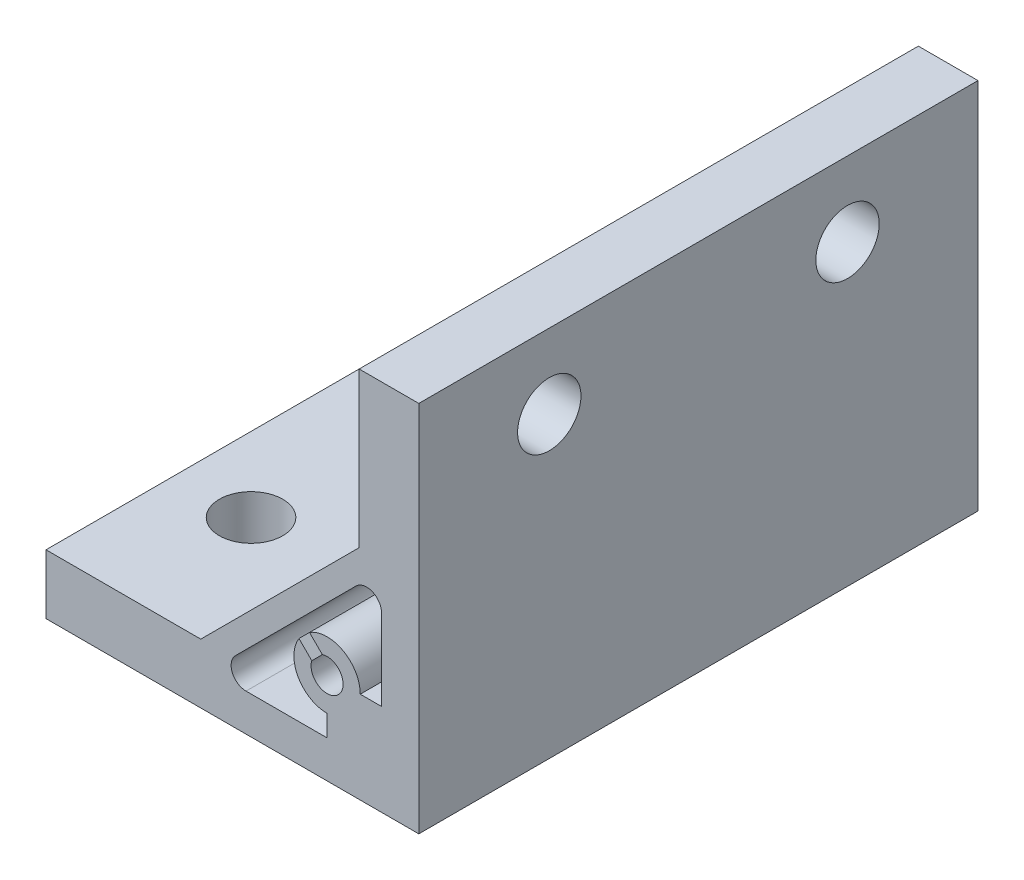
SolidWorks part; units mm, degrees
ref_plane "前视基准面" through (0, 0, 0) normal (0, 0, 1) x (1, 0, 0)
ref_plane "上视基准面" through (0, 0, 0) normal (0, 1, 0) x (1, 0, 0)
ref_plane "右视基准面" through (0, 0, 0) normal (1, 0, 0) x (0, 0, -1)
sketch "草图1" plane through (0, 0, 0) normal (0, 0, 1) x (1, 0, 0)
  line B0 (0, 0) -> (50, 0)
  line B1 (50, 0) -> (50, 50)
  line B2 (0, 8) -> (20.7574, 8)
  line B3 (42, 29.2426) -> (42, 50)
  line B4 (0, 8) -> (0, 0)
  line B5 (42, 50) -> (50, 50)
  line B6 (37.0613, 14.3529) -> (35.341, 16.0733)
  line B7 (35.6471, 12.9387) -> (33.9267, 14.659)
  line B8 (25.4142, 8.4142) -> (41.5858, 24.5858)
  line B9 (20.7574, 8) -> (42, 29.2426)
  line B10 (26.8284, 5) -> (37.7, 5)
  line B11 (45, 23.1716) -> (45, 12.3)
  line B12 (37.7, 5) -> (37.7, 7.85)
  line B13 (42.15, 12.3) -> (45, 12.3)
  arc B14 (33.9267, 14.659) -> (37.7, 7.85) centre (37.7, 12.3) ccw
  arc B15 (42.15, 12.3) -> (35.341, 16.0733) centre (37.7, 12.3) ccw
  arc B16 (35.6471, 12.9387) -> (37.0613, 14.3529) centre (37.7, 12.3) ccw
  arc B17 (25.4142, 8.4142) -> (26.8284, 5) centre (26.8284, 7) ccw
  arc B18 (45, 23.1716) -> (41.5858, 24.5858) centre (43, 23.1716) ccw
sketch_block_instance "A$C19004297-1"
sketch_block "A$C19004297"
extrude "凸台-拉伸1" add sketch "草图1" along normal mid plane 75
sketch "草图3" plane through (0, 8, 0) normal (0, 1, 0) x (1, 0, 0)
  line L0 (0, -37.5) -> (0, 37.5) construction
  line L1 (0, 0) -> (17.1936, 0) construction
  circle A0 centre (10, 20) radius 4.25
  circle A1 centre (10, -20) radius 4.25
  dimension "D1" = 10
  dimension "D2" = 20
extrude "切除-拉伸1" cut sketch "草图3" against normal through all
sketch "草图4" plane through (6.3787, -6.3787, 0) normal (-0.7071, 0.7071, 0) x (0, 0, 1)
  line L0 (-37.5, 35.3553) -> (37.5, 35.3553) construction
  line L1 (-37.5, 50.3762) -> (-37.5, 20.3345) construction
  line L2 (37.5, 50.3762) -> (37.5, 20.3345) construction
ref_plane "基准面2" through (25, 25, 0) normal (0.7071, 0.7071, 0) x (0, 0, -1)
mirror "镜向1" about plane through (25, 25, 0) normal (0.7071, 0.7071, 0) of "切除-拉伸1"
